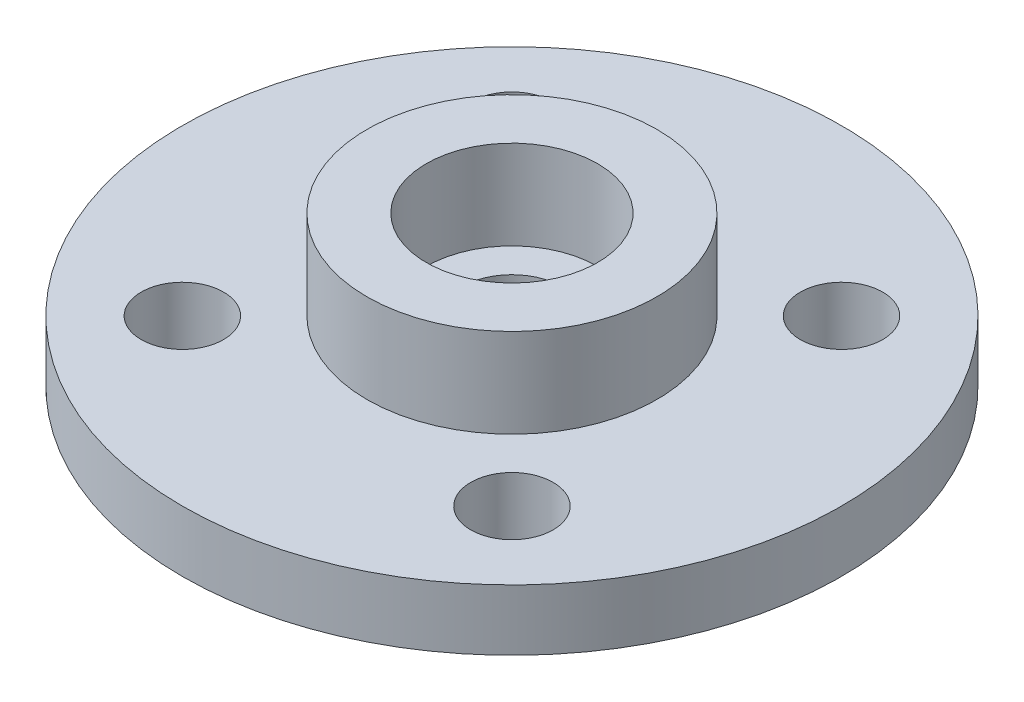
SolidWorks part; units mm, degrees
ref_plane "Front" through (0, 0, 0) normal (0, 0, 1) x (1, 0, 0)
ref_plane "Top" through (0, 0, 0) normal (0, 1, 0) x (1, 0, 0)
ref_plane "Right" through (0, 0, 0) normal (1, 0, 0) x (0, 0, -1)
sketch "Sketch1" plane through (0, 0, 0) normal (0, 1, 0) x (1, 0, 0)
  line L1 (-5, -5) -> (5, -5)
  line L2 (-5, -5) -> (-5, 5)
  line L3 (-5, 5) -> (5, 5)
  line L4 (5, -5) -> (5, 5)
  line L5 (-5, -5) -> (5, 5) construction
  line L6 (-5, 5) -> (5, -5) construction
  circle A0 centre (0, 0) radius 1.53
  circle A1 centre (0, 0) radius 10
  circle A2 centre (-5, 5) radius 1.25
  circle A3 centre (5, 5) radius 1.25
  circle A4 centre (5, -5) radius 1.25
  circle A5 centre (-5, -5) radius 1.25
  dimension "D1" = 3.06
  dimension "D2" = 20
  dimension "D4" = 2.5
  dimension "D3" = 10
extrude "Boss-Extrude1" add sketch "Sketch1" along normal blind 1.85 contours A5 L1 A4 L4 A3 L3 A2 L2 A0 | A1 A5 L2 A2 L3 A3 L4 A4 L1
sketch "Sketch2" plane through (0, 1.85, 0) normal (0, 1, 0) x (1, 0, 0)
  circle A0 centre (0, 0) radius 2.6
  circle A1 centre (0, 0) radius 4.4
  dimension "D1" = 5.2
  dimension "D2" = 8.8
extrude "Boss-Extrude2" add sketch "Sketch2" along normal blind 2.7
